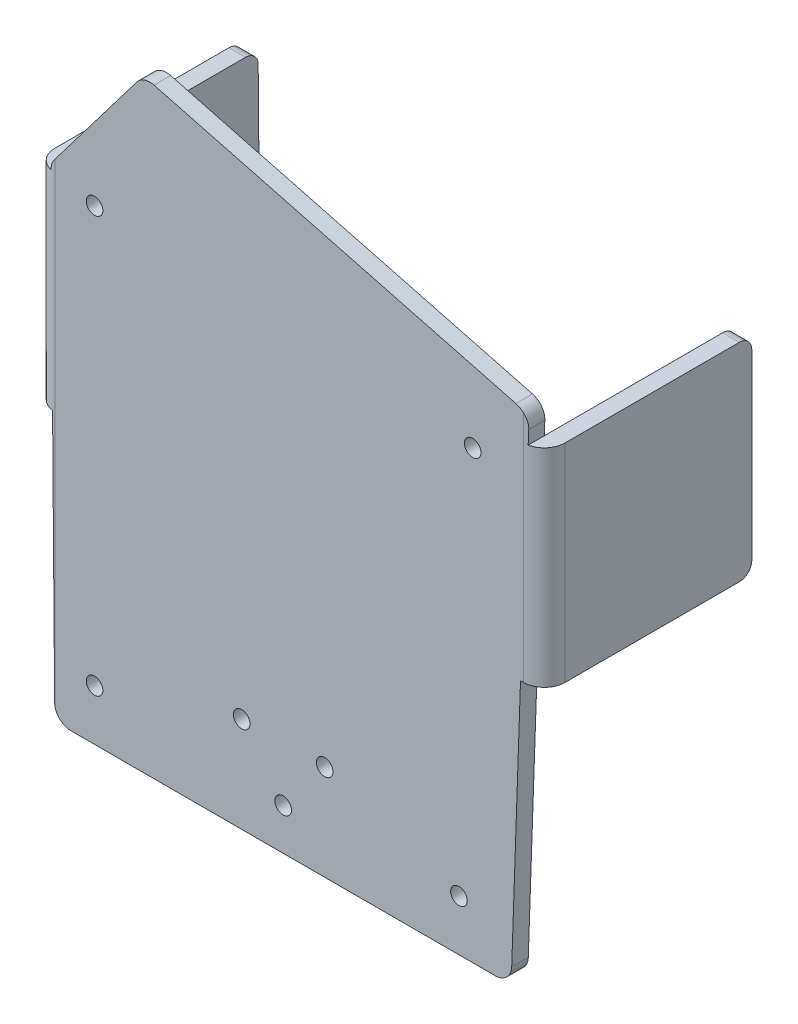
SolidWorks part; units mm, degrees
ref_plane "Front Plane" through (0, 0, 0) normal (0, 0, 1) x (1, 0, 0)
ref_plane "Top Plane" through (0, 0, 0) normal (0, 1, 0) x (1, 0, 0)
ref_plane "Right Plane" through (0, 0, 0) normal (1, 0, 0) x (0, 0, -1)
sketch "Sketch1" plane through (0, 0, 0) normal (0, 0, 1) x (1, 0, 0)
  line L0 (-1.9146, 0) -> (-53.0346, 0)
  line L4 (0.0668, 1.9134) -> (2.0597, 58.982)
  line L6 (-55.0172, 1.9653) -> (-55.5002, 57.3229)
  line L8 (-55.0966, 58.5393) -> (-45.1183, 71.6788)
  line L9 (-43.0368, 72.3976) -> (0.5808, 60.969)
  line L10 (-32.4746, 11.5) -> (-22.4746, 11.5) construction
  arc A0 (-1.9146, 0) -> (0.0668, 1.9134) centre (-1.9146, 1.9826) ccw
  arc A1 (-53.0346, 0) -> (-55.0172, 1.9653) centre (-53.0346, 1.9826) cw
  arc A2 (2.0597, 58.982) -> (0.5808, 60.969) centre (0.0783, 59.0511) ccw
  arc A3 (-45.1183, 71.6788) -> (-43.0368, 72.3976) centre (-43.5393, 70.4797) cw
  arc A4 (-55.5002, 57.3229) -> (-55.0966, 58.5393) centre (-53.5177, 57.3402) cw
  circle A5 centre (-27.4746, 5) radius 1
  circle A6 centre (-22.4746, 11.5) radius 1
  circle A7 centre (-32.4746, 11.5) radius 1
  circle A8 centre (-6.2922, 6.1355) radius 1
  circle A9 centre (-50.2068, 6.1355) radius 1
  circle A10 centre (-50.2068, 56.2185) radius 1
  circle A11 centre (-4.635, 53.7327) radius 1
  point P8 (0, 0)
  point P12 (-55, 0)
  point P15 (2.115, 60.567)
  point P18 (-44.3175, 72.7331)
  point P21 (-55.5062, 58)
  point P27 (-27.4746, 0)
  dimension "D9" = 2
  dimension "D10" = 5
  dimension "D14" = 2
  dimension "D15" = 2
  dimension "D16" = 2
  dimension "D17" = 2
  dimension "D1" = 55
  dimension "D2" = 58
  dimension "D3" = 92
  dimension "D4" = 48
  dimension "D5" = 18.5
  dimension "D6" = 90.5
  dimension "D11" = 5
  dimension "D12" = 6.5
  dimension "D13" = 5
extrude "Boss-Extrude1" add sketch "Sketch1" along normal blind 2
sketch "Sketch2" plane through (0, 0, 0) normal (0, 0, -1) x (-1, 0, 0)
  line L0 (55.5002, 57.3229) -> (55.2821, 32.3229)
  line L1 (55.5002, 57.3229) -> (55.0172, 1.9653) construction
  line L2 (55.2821, 32.3229) -> (57.5002, 32.3229)
  line L3 (57.5002, 32.3229) -> (57.5002, 57.3229)
  line L4 (57.5002, 57.3229) -> (55.5002, 57.3229)
  line L5 (-1.1287, 32.3229) -> (-4.0018, 32.3229)
  line L6 (-0.0668, 1.9134) -> (-2.0597, 58.982) construction
  line L7 (-4.0018, 32.3229) -> (-4.0018, 57.3229)
  line L8 (-4.0018, 57.3229) -> (-2.0018, 57.3229)
  line L9 (-2.0018, 57.3229) -> (-1.1287, 32.3229)
  line L10 (55.5002, 57.3229) -> (57.5002, 57.3229)
  line L11 (57.5002, 32.3229) -> (55.2821, 32.3229)
  line L13 (-1.1287, 32.3229) -> (-4.0018, 32.3229)
  line L14 (-4.0018, 57.3229) -> (-2.0018, 57.3229)
  point P11 (-2.5653, 32.3229)
  line M10 (55.0172, 1.9653) -> (55.5002, 57.3229)
  line M16 (-2.0597, 58.982) -> (-0.0668, 1.9134)
  dimension "D1" = 25
  dimension "D2" = 25
  dimension "D3" = 2
  dimension "D4" = 2
extrude "Boss-Extrude2" add sketch "Sketch2" along normal blind 23 separate body contours L8 L7 L5 M16 | L3 L4 L2 M10
sketch "Sketch3" plane through (0, 0, 0) normal (0, 0, 1) x (1, 0, 0)
  line L0 (-57.5002, 57.3229) -> (-55.5002, 57.3229)
  line L1 (-55.2821, 32.3229) -> (-55.5002, 57.3229) construction
  line L2 (-57.5002, 57.3229) -> (-55.5002, 57.3229) construction
  line L3 (-55.5002, 57.3229) -> (-55.2821, 32.3229)
  line L4 (-55.2821, 32.3229) -> (-57.5002, 32.3229)
  line L5 (-57.5002, 32.3229) -> (-57.5002, 57.3229)
  line L6 (2.0018, 57.3229) -> (4.0018, 57.3229)
  line L7 (4.0018, 57.3229) -> (4.0018, 32.3229)
  line L8 (4.0018, 32.3229) -> (1.1287, 32.3229)
  line L9 (0.0668, 1.9134) -> (2.0597, 58.982) construction
  line L10 (2.0018, 57.3229) -> (1.1287, 32.3229) construction
  line L11 (1.1287, 32.3229) -> (2.0018, 57.3229)
extrude "Boss-Extrude3" add sketch "Sketch3" along normal up to surface (2 mm away) up to face at (-49.2068, 56.2185, 2)
fillet "Fillet1" radius 2.5 2 edges at (4.0018, 44.8229, 2) (-57.5002, 44.8229, 2)
fillet "Fillet2" radius 1.5 4 edges at (2.5653, 32.3229, -23) (-56.3912, 32.3229, -23) (-56.5002, 57.3229, -23) (3.0018, 57.3229, -23)
